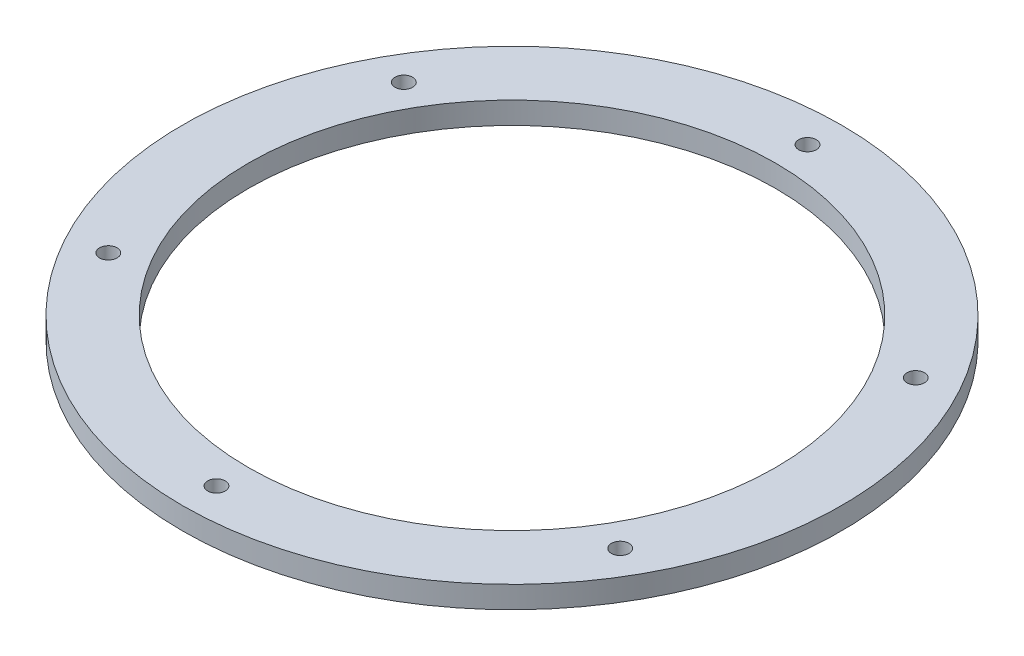
SolidWorks part; units mm, degrees
ref_plane "Спереди" through (0, 0, 0) normal (0, 0, 1) x (1, 0, 0)
ref_plane "Сверху" through (0, 0, 0) normal (0, 1, 0) x (1, 0, 0)
ref_plane "Справа" through (0, 0, 0) normal (1, 0, 0) x (0, 0, -1)
sketch "Эскиз1" plane through (0, 0, 0) normal (0, 1, 0) x (1, 0, 0)
  circle A0 centre (0, 0) radius 75
  circle A1 centre (0, 0) radius 60
extrude "Бобышка-Вытянуть1" add sketch "Эскиз1" along normal blind 5
sketch "Эскиз2" plane through (0, 5, 0) normal (0, 1, 0) x (1, 0, 0)
  line L0 (0, -940) -> (0, 49060) construction
  circle A1 centre (0, 67.2541) radius 2
  circle A2 centre (58.2437, 33.627) radius 2
  circle A3 centre (58.2437, -33.627) radius 2
  circle A4 centre (0, -67.2541) radius 2
  circle A5 centre (-58.2437, -33.627) radius 2
  circle A6 centre (-58.2437, 33.627) radius 2
  point P16 (0, 0)
  dimension "D1" = 6
extrude "Вырез-Вытянуть1" cut sketch "Эскиз2" against normal through all
